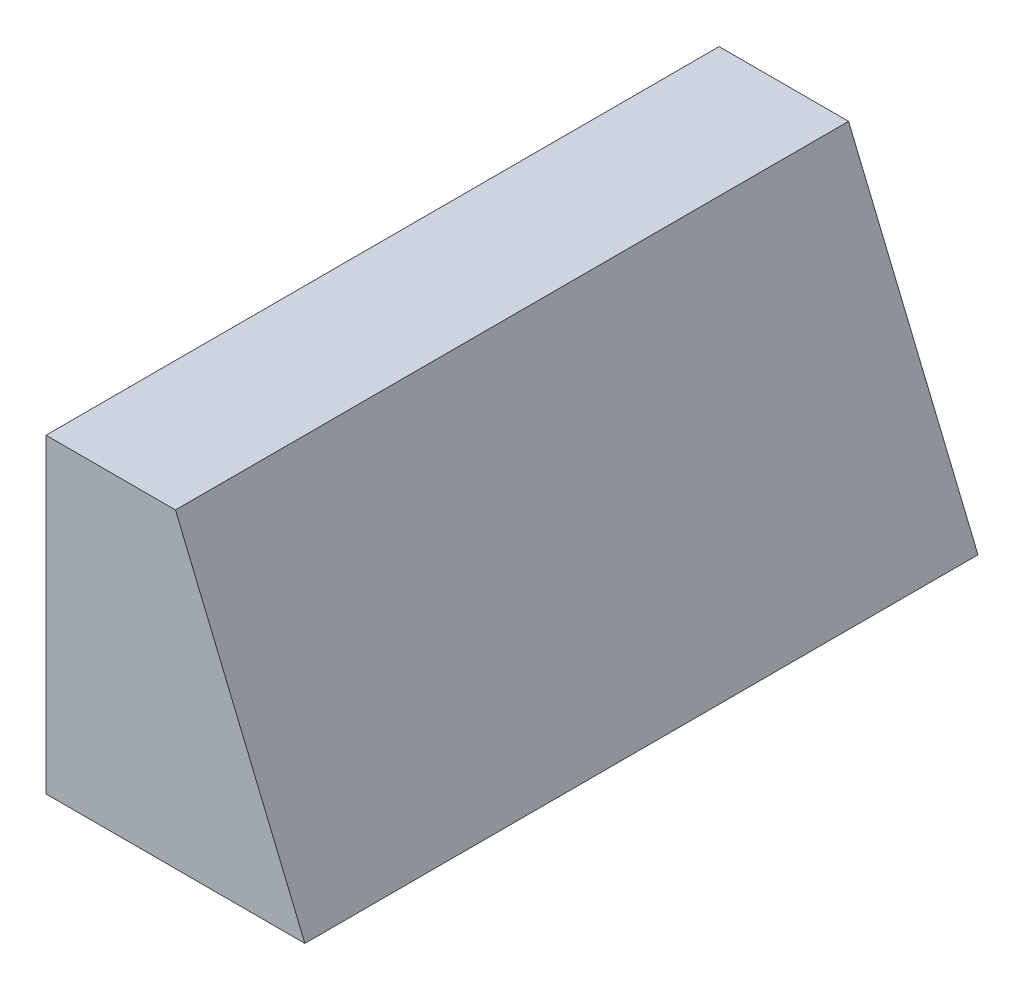
SolidWorks part; units mm, degrees
ref_plane "Front Plane" through (0, 0, 0) normal (0, 0, 1) x (1, 0, 0)
ref_plane "Top Plane" through (0, 0, 0) normal (0, 1, 0) x (1, 0, 0)
ref_plane "Right Plane" through (0, 0, 0) normal (1, 0, 0) x (0, 0, -1)
sketch "Sketch1" plane through (0, 0, 0) normal (0, 0, 1) x (1, 0, 0)
  line L0 (-5.3852, 5.4064) -> (-5.3852, -6.5936)
  line L1 (-5.3852, -6.5936) -> (4.6148, -6.5936)
  line L2 (-5.3852, 5.4064) -> (-0.3852, 5.4064)
  line L3 (-0.3852, 5.4064) -> (4.6148, -6.5936)
  dimension "D1" = 12
  dimension "D2" = 5
  dimension "D3" = 10
extrude "Boss-Extrude1" add sketch "Sketch1" along normal blind 26
